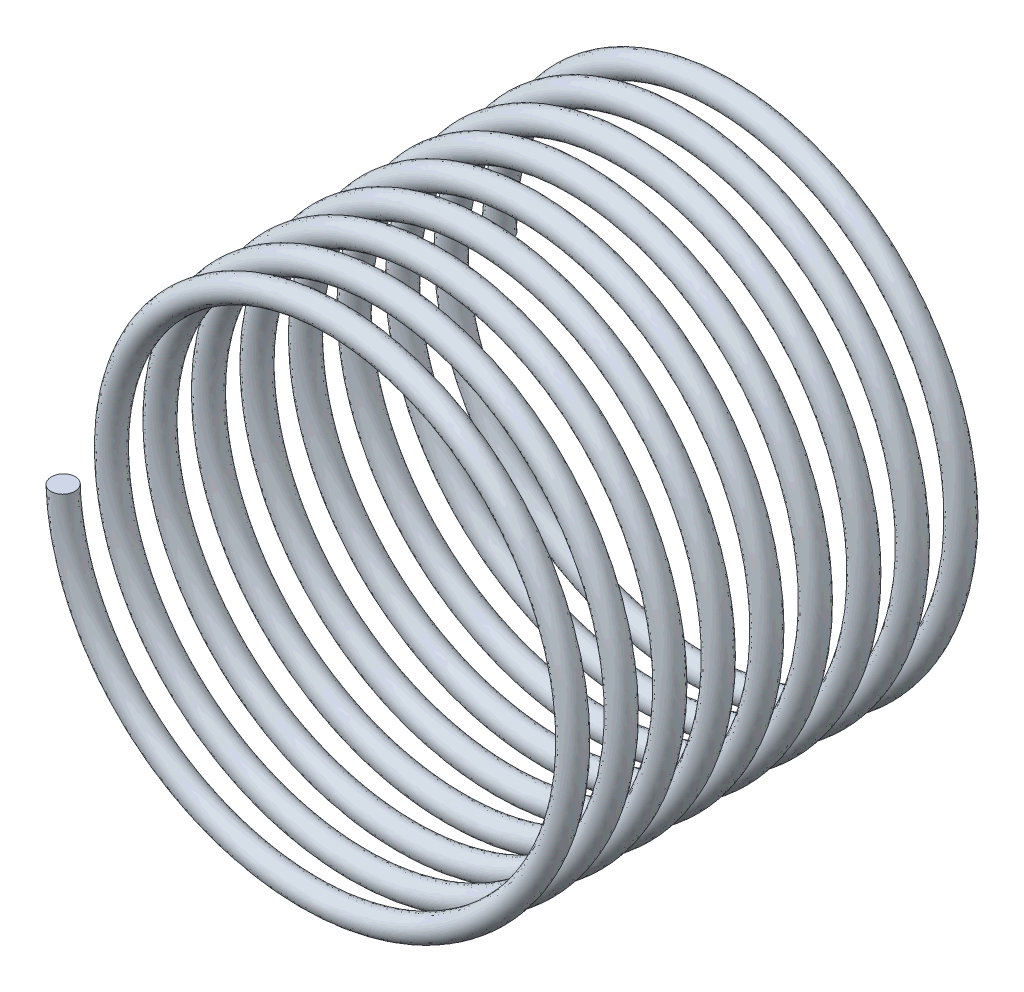
SolidWorks part; units mm, degrees
ref_plane "Front Plane" through (0, 0, 0) normal (0, 0, 1) x (1, 0, 0)
ref_plane "Top Plane" through (0, 0, 0) normal (0, 1, 0) x (1, 0, 0)
ref_plane "Right Plane" through (0, 0, 0) normal (1, 0, 0) x (0, 0, -1)
sketch "Sketch1" plane through (0, 0, 0) normal (0, 0, 1) x (1, 0, 0)
  circle A0 centre (0, 0) radius 50
  dimension "D1" = 100
curve "Helix/Spiral1" pitch 10 height 90 turns 9
sweep "Sweep1" add path "Helix/Spiral1" circular profile diameter 5 parameters "D3"=5
